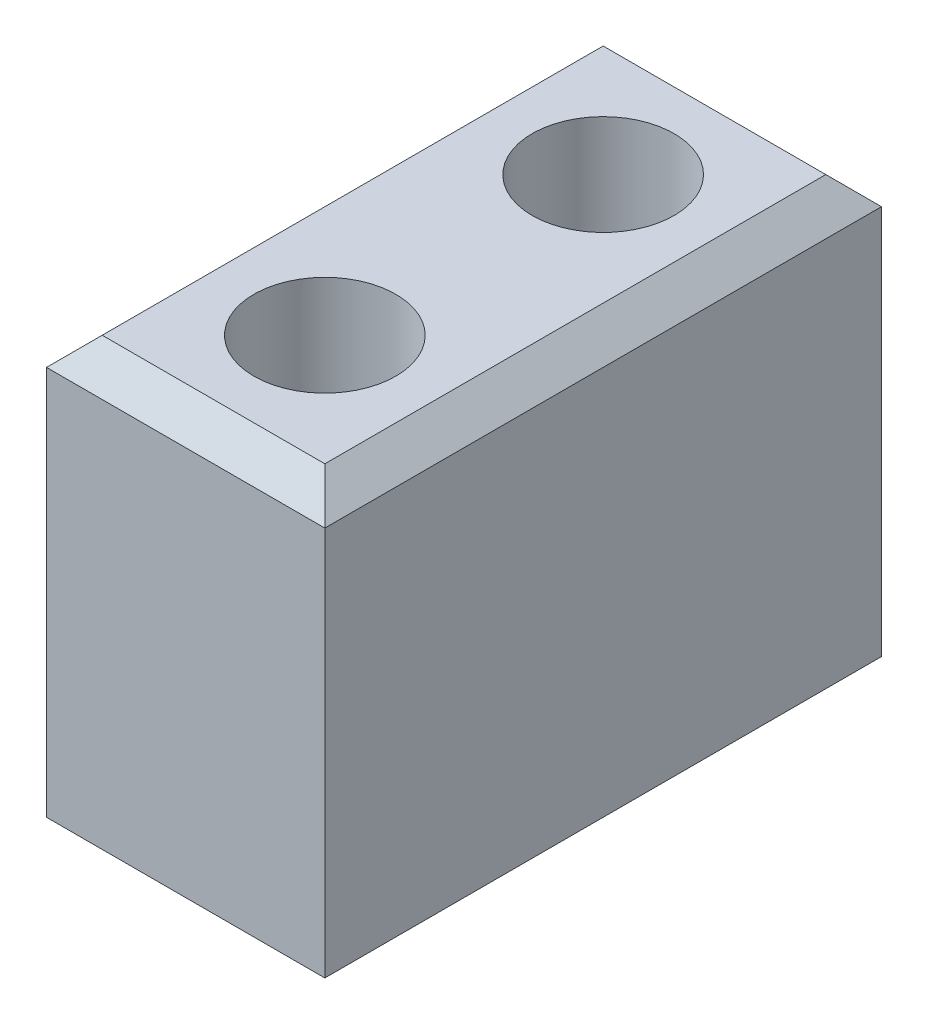
SolidWorks part; units mm, degrees
material "AISI 1020"
ref_plane "Plano frontal" through (0, 0, 0) normal (0, 0, 1) x (1, 0, 0)
ref_plane "Plano superior" through (0, 0, 0) normal (0, 1, 0) x (1, 0, 0)
ref_plane "Plano direito" through (0, 0, 0) normal (1, 0, 0) x (0, 0, -1)
sketch "Esboço1" plane through (0, 0, 0) normal (0, 1, 0) x (1, 0, 0)
  line L1 (-10, -20) -> (10, -20)
  line L2 (-10, -20) -> (-10, 20)
  line L3 (-10, 20) -> (10, 20)
  line L4 (10, -20) -> (10, 20)
  line L5 (-10, -20) -> (10, 20) construction
  line L6 (-10, 20) -> (10, -20) construction
  point P0 (0, 0)
  dimension "D1" = 20
  dimension "D2" = 40
extrude "Ressalto-extrusão1" add sketch "Esboço1" along normal mid plane 30
hole_wizard "Furo roscado de M121" positions "Esboço4" profile "Esboço5" tap size "M12" standard "DIN" end condition through all
sketch "Esboço4" plane through (0, 15, 0) normal (0, 1, 0) x (1, 0, 0)
  line L0 (10, 20) -> (-10, 20) construction
  line L1 (10, -20) -> (10, 20) construction
  point P0 (0, 10)
  dimension "D1" = 10
  dimension "D2" = 10
cosmetic thread "Rosca de furo1" parameters "D2"=12
sketch "Esboço5" plane through (0, 15, -10) normal (1, 0, 0) x (0, 0, 1)
  line L0 (0, 0) -> (0, 30)
  line L1 (0, 30) -> (5.1, 30)
  line L2 (5.1, 30) -> (5.1, 0)
  line L5 (5.1, 0) -> (0, 0)
  line L11 (0, -6.35) -> (0, 107.95) construction
  dimension "Thru Tap Drill Dia." = 10.2
  dimension "Thru Tap Drill Depth" = 30
hole_wizard "Furo roscado de M122" positions "Esboço6" profile "Esboço7" tap size "M12" standard "DIN"
sketch "Esboço6" plane through (0, 15, 0) normal (0, 1, 0) x (1, 0, 0)
  line L0 (-10, -20) -> (10, -20) construction
  line L1 (10, -20) -> (10, 20) construction
  point P0 (0, -10)
  dimension "D1" = 10
  dimension "D2" = 10
sketch "Esboço7" plane through (0, 15, 10) normal (1, 0, 0) x (0, 0, 1)
  line L0 (0, 0) -> (0, 28.0644)
  line L1 (0, 28.0644) -> (5.1, 25)
  line L2 (5.1, 25) -> (5.1, 0)
  line L5 (5.1, 0) -> (0, 0)
  line L10 (0, 28.0644) -> (-5.1, 25) construction
  line L11 (0, -6.35) -> (0, 107.95) construction
  dimension "Tap Drill Dia." = 10.2
  dimension "Tap Drill Depth" = 25
  dimension "Drill Angle" = 118
cosmetic thread "Rosca de furo2" parameters "D1"=20, "D2"=12
chamfer "Chanfro2" distance 2 angle 45 4 edges at (-10, 15, 0) (0, 15, -20) (10, 15, 0) (0, 15, 20)
